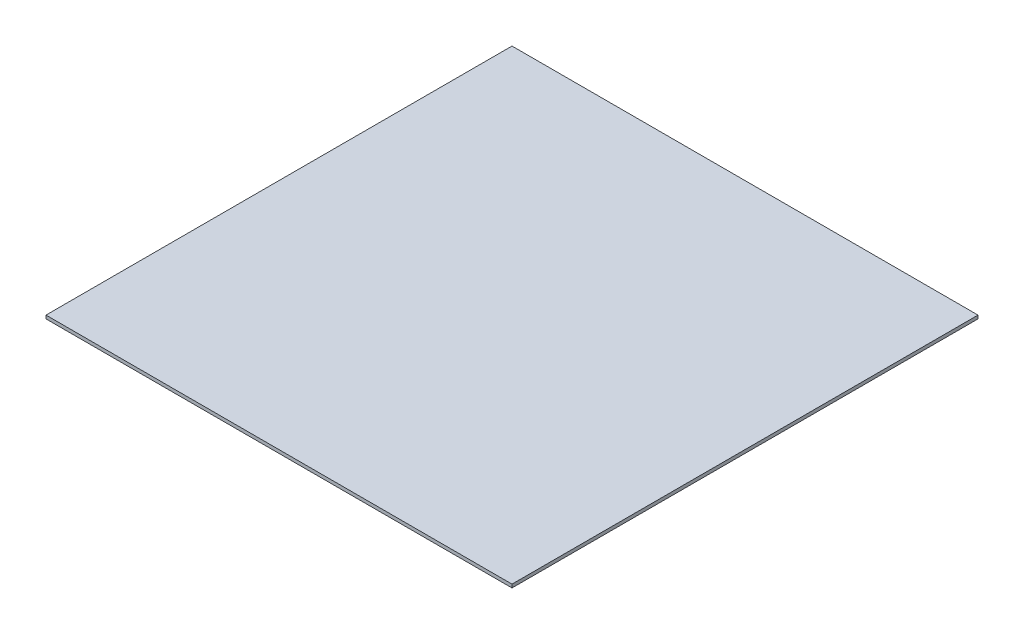
SolidWorks part; units mm, degrees
ref_plane "Front Plane" through (0, 0, 0) normal (0, 0, 1) x (1, 0, 0)
ref_plane "Top Plane" through (0, 0, 0) normal (0, 1, 0) x (1, 0, 0)
ref_plane "Right Plane" through (0, 0, 0) normal (1, 0, 0) x (0, 0, -1)
sketch "Sketch1" plane through (0, 0, 0) normal (0, 1, 0) x (1, 0, 0)
  line L1 (-69.85, 69.85) -> (69.85, 69.85)
  line L2 (-69.85, 69.85) -> (-69.85, -69.85)
  line L3 (-69.85, -69.85) -> (69.85, -69.85)
  line L4 (69.85, 69.85) -> (69.85, -69.85)
  line L5 (-69.85, 69.85) -> (69.85, -69.85) construction
  line L6 (-69.85, -69.85) -> (69.85, 69.85) construction
  point P0 (0, 0)
  dimension "D1" = 139.7
extrude "Boss-Extrude1" add sketch "Sketch1" along normal blind 1
